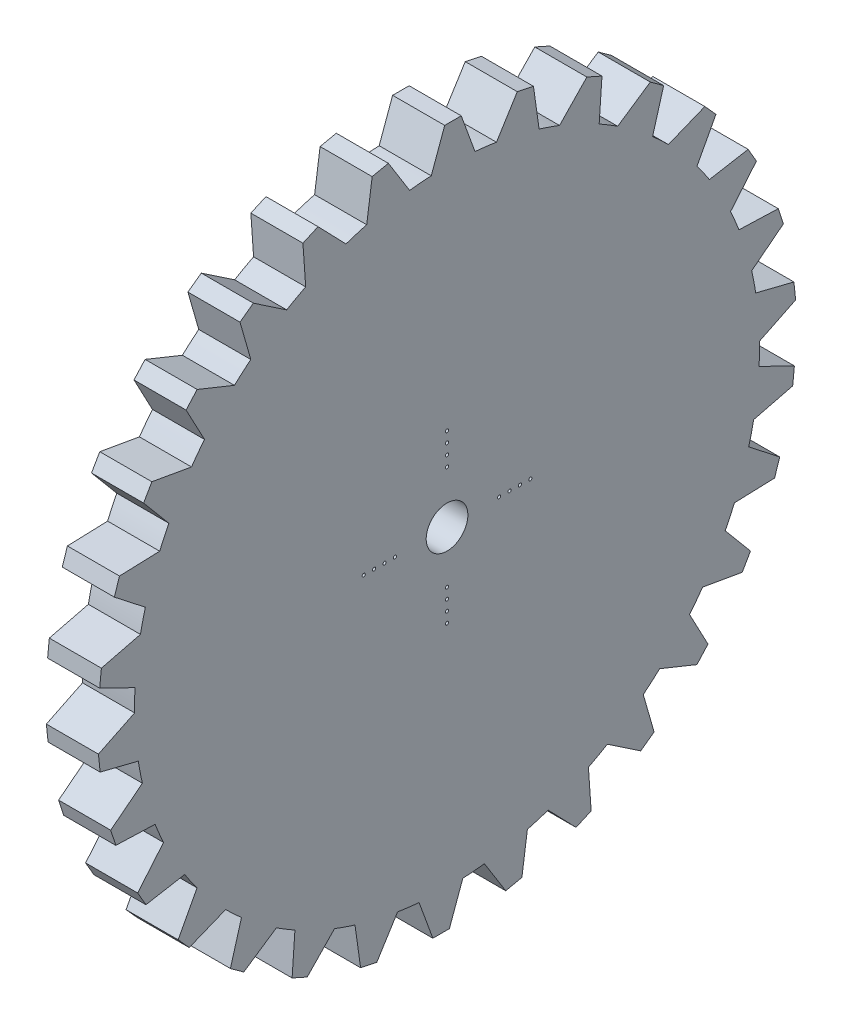
SolidWorks part; units mm, degrees
ref_plane "Front Plane" through (0, 0, 0) normal (0, 0, 1) x (1, 0, 0)
ref_plane "Top Plane" through (0, 0, 0) normal (0, 1, 0) x (1, 0, 0)
ref_plane "Right Plane" through (0, 0, 0) normal (1, 0, 0) x (0, 0, -1)
sketch "Sketch1" plane through (0, 0, 0) normal (1, 0, 0) x (0, 0, -1)
  circle A0 centre (0, 0) radius 30
  circle A1 centre (0, 0) radius 2
  dimension "D1" = 60
  dimension "D3" = 4
  dimension "D2" = 28
extrude "Boss-Extrude2" add sketch "Sketch1" along normal blind 5
sketch "Sketch2" plane through (5, 0, 0) normal (1, 0, 0) x (0, 0, -1)
  circle A0 centre (0, 5) radius 0.15
  dimension "D1" = 0.3
  dimension "D2" = 5
extrude "Cut-Extrude1" cut sketch "Sketch2" against normal through all
pattern_linear "LPattern1" count 4 spacing 1 along (0, 1, 0) of "Cut-Extrude1"
pattern_circular "CirPattern1" count 4 over 360 about axis through (0, 0, 0) along (1, 0, 0) of "LPattern1", "Cut-Extrude1"
sketch "Sketch7" plane through (5, 0, 0) normal (1, 0, 0) x (0, 0, -1)
  line L0 (-1.6815, 29.5092) -> (2.8185, 29.5092)
  line L1 (2.8185, 29.5092) -> (1.3626, 33.5092)
  line L2 (1.3626, 33.5092) -> (-0.2256, 33.5092)
  line L3 (-0.2256, 33.5092) -> (-1.6815, 29.5092)
  dimension "D1" = 70
  dimension "D2" = 70
  dimension "D3" = 4
  dimension "D4" = 4.5
extrude "Boss-Extrude3" add sketch "Sketch7" against normal blind 5
pattern_circular "CirPattern2" count 30 over 360 about axis through (0, 0, 0) along (1, 0, 0) of "Boss-Extrude3"
